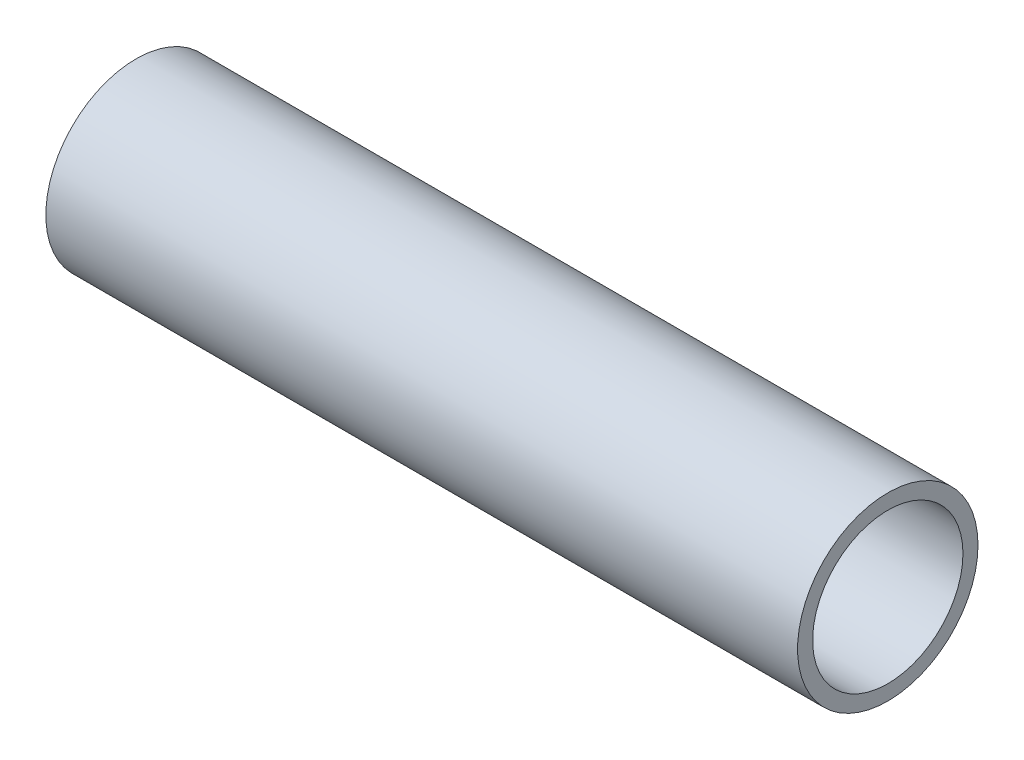
SolidWorks part; units mm, degrees
material "Alloy Steel"
ref_plane "Front" through (0, 0, 0) normal (0, 0, 1) x (1, 0, 0)
ref_plane "Top" through (0, 0, 0) normal (0, 1, 0) x (1, 0, 0)
ref_plane "Right" through (0, 0, 0) normal (1, 0, 0) x (0, 0, -1)
sketch "Sketch1" plane through (0, 0, 0) normal (1, 0, 0) x (0, 0, -1)
  circle A0 centre (0, 0) radius 6
  circle A1 centre (0, 0) radius 5
  dimension "D1" = 10
  dimension "D2" = 12
extrude "Extrude1" add sketch "Sketch1" along normal mid plane 50
